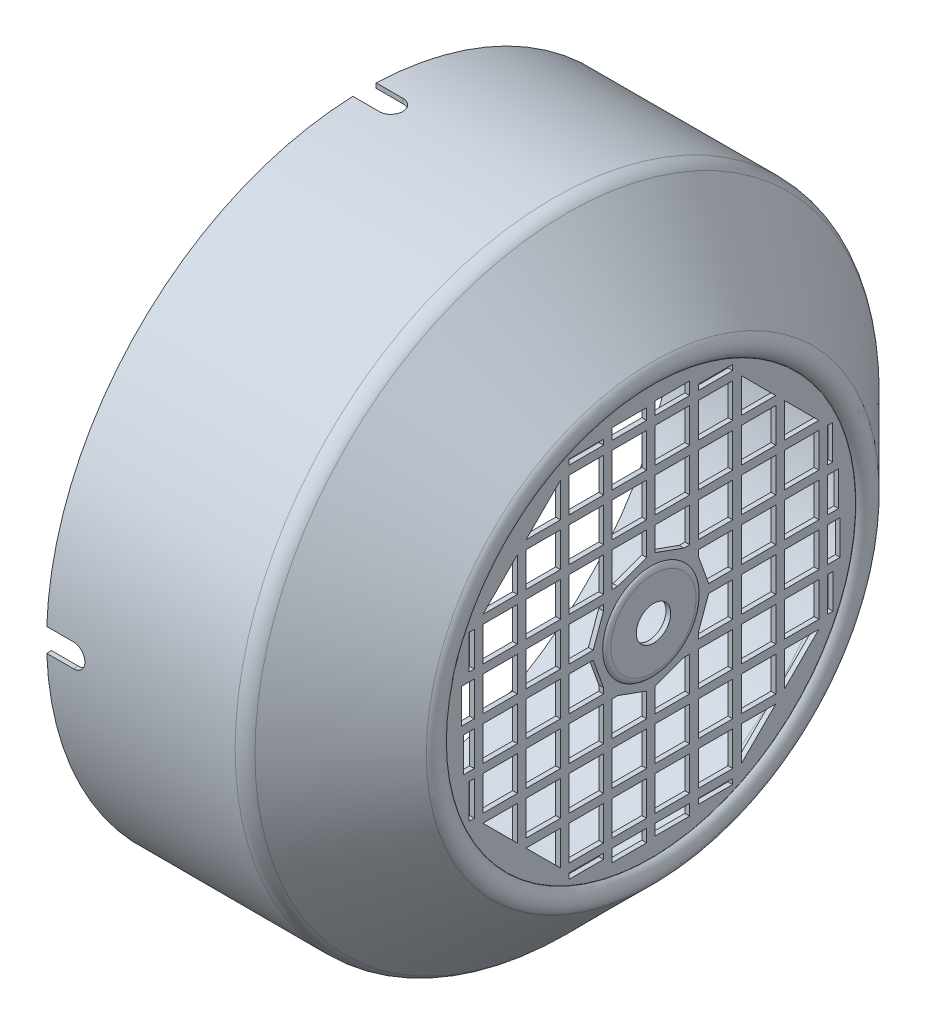
SolidWorks part; units mm, degrees
ref_plane "Plan de face" through (0, 0, 0) normal (0, 0, 1) x (1, 0, 0)
ref_plane "Plan de dessus" through (0, 0, 0) normal (0, 1, 0) x (1, 0, 0)
ref_plane "Plan de droite" through (0, 0, 0) normal (1, 0, 0) x (0, 0, -1)
sketch "Esquisse1" plane through (0, 0, 0) normal (0, 0, 1) x (1, 0, 0)
  line L0 (-18.5477, 0) -> (43.015, 0) construction
  line L1 (0, 4) -> (0, 9.9)
  line L2 (-0.9673, 9.9) -> (0.1952, 9.9) construction
  line L3 (-0.6, 10.5) -> (-0.6, 9.7263) construction
  line L5 (-0.6, 10.5) -> (-0.6, 47.5)
  line L6 (0.1556, 51.8052) -> (-19.7341, 71.6949)
  line L7 (-22.2089, 72.72) -> (-66, 72.72)
  arc A0 (0, 9.9) -> (-0.6, 10.5) centre (-0.6, 9.9) ccw
  arc A1 (-0.6, 47.5) -> (-0.1059, 48.4704) centre (0.6, 47.5) cw
  arc A2 (-0.1059, 48.4704) -> (0.1556, 51.8052) centre (-1.4, 50.2495) ccw
  arc A3 (-19.7341, 71.6949) -> (-22.2089, 72.72) centre (-22.2089, 69.22) ccw
  dimension "D3" = 0.6
  dimension "D6" = 1.2
  dimension "D7" = 2.2
  dimension "D10" = 7
  dimension "D11" = 64.6
  dimension "D1" = 8
  dimension "D2" = 21
  dimension "D4" = 95
  dimension "D5" = 135
  dimension "D8" = 0.8
  dimension "D9" = 145.44
revolve "Révol.-Mince1" add sketch "Esquisse1" angle 360 about L0
sketch "Esquisse2" plane through (0.5, 0, 0) normal (1, 0, 0) x (0, 0, -1)
  line L0 (0, 50.1333) -> (0, -49.9158) construction
  line L1 (-50.8687, 0) -> (49.5666, 0) construction
  line L2 (-46.04, 20) -> (47.4421, 20) construction
  line L3 (-9, 29) -> (-1, 29)
  line L4 (-9, 29) -> (-9, 21)
  line L5 (-9, 21) -> (-1, 21)
  line L6 (-1, 29) -> (-1, 21)
  line L7 (-19, 29) -> (-19, 21)
  line L8 (-37.3485, 30) -> (37.978, 30) construction
  line L9 (-10, 48.0087) -> (-10, 0) construction
  line L10 (-11, 21) -> (-19, 21)
  line L11 (-11, 29) -> (-11, 21)
  line L12 (-11, 29) -> (-19, 29)
  line L13 (-1, 13.4124) -> (-1, 19)
  line L14 (-9, 11) -> (-9, 19)
  line L15 (-9, 19) -> (-1, 19)
  line L16 (-9, 11) -> (-7.7249, 11)
  line L17 (-11, 11) -> (-19, 11)
  line L18 (-19, 11) -> (-19, 19)
  line L19 (-11, 19) -> (-19, 19)
  line L20 (-11, 11) -> (-11, 19)
  line L21 (-19, 41) -> (-19, 42.2143)
  line L22 (-11, 41) -> (-19, 41)
  line L23 (-19, 42.2143) -> (-11, 42.2143)
  line L24 (-11, 42.2143) -> (-11, 41)
  line L25 (-9, 41) -> (-9, 43.5663)
  line L26 (-9, 41) -> (-1, 41)
  line L27 (-9, 43.5663) -> (-1, 43.5663)
  line L28 (-1, 43.5663) -> (-1, 41)
  line L29 (-11, 31) -> (-19, 31)
  line L30 (-11, 31) -> (-11, 39)
  line L31 (-11, 39) -> (-19, 39)
  line L32 (-19, 31) -> (-19, 39)
  line L33 (-1, 31) -> (-1, 39)
  line L34 (-9, 39) -> (-1, 39)
  line L35 (-9, 31) -> (-9, 39)
  line L36 (-9, 31) -> (-1, 31)
  line L37 (-49.3235, 10) -> (49.5666, 10) construction
  line L38 (-11, 9) -> (-11, 7.6741)
  line L39 (-13.4124, 1) -> (-19, 1)
  line L40 (-19, 9) -> (-19, 1)
  line L41 (-11, 9) -> (-19, 9)
  line L42 (-20, 44.3389) -> (-20, -2.7884) construction
  line L43 (-29, 9) -> (-21, 9)
  line L44 (-21, 9) -> (-21, 1)
  line L45 (-29, 1) -> (-21, 1)
  line L46 (-29, 9) -> (-29, 1)
  line L47 (-21, 39) -> (-29, 31)
  line L48 (-31, 29) -> (-39, 21)
  line L49 (-41, 19) -> (-42.2723, 19)
  line L50 (-42.2723, 19) -> (-42.2723, 11)
  line L51 (-21, 31) -> (-21, 39)
  line L52 (-42.2723, 11) -> (-41, 11)
  line L53 (-41, 9) -> (-43.9467, 9)
  line L54 (-29, 31) -> (-21, 31)
  line L55 (-29, 11) -> (-29, 19)
  line L56 (-29, 19) -> (-21, 19)
  line L57 (-21, 11) -> (-21, 19)
  line L58 (-29, 11) -> (-21, 11)
  line L59 (-31, 11) -> (-39, 11)
  line L60 (-39, 11) -> (-39, 19)
  line L61 (-31, 19) -> (-39, 19)
  line L62 (-31, 11) -> (-31, 19)
  line L63 (-29, 29) -> (-21, 29)
  line L64 (-29, 29) -> (-29, 21)
  line L65 (-29, 21) -> (-21, 21)
  line L66 (-21, 29) -> (-21, 21)
  line L67 (-43.9467, 9) -> (-43.9467, 1)
  line L68 (-31, 21) -> (-39, 21)
  line L69 (-31, 29) -> (-31, 21)
  line L70 (-43.9467, 1) -> (-41, 1)
  line L71 (-30, 40.5595) -> (-30, -1.5894) construction
  line L72 (-31, 9) -> (-31, 1)
  line L73 (-31, 1) -> (-39, 1)
  line L74 (-39, 9) -> (-39, 1)
  line L75 (-31, 9) -> (-39, 9)
  line L76 (-11, 7.6741) -> (-13.4124, 1)
  line L77 (-41, 9) -> (-41, 1)
  line L78 (-7.7249, 11) -> (-1, 13.4124)
  line L82 (-41, 11) -> (-41, 19)
  dimension "D1" = 8
  dimension "D2" = 8
  dimension "D3" = 2
  dimension "D4" = 42
  dimension "D5" = 2
  dimension "D6" = 2
  dimension "D7" = 2
  dimension "D8" = 2
  dimension "D9" = 2
extrude "Enlèv. mat.-Extru.1" cut sketch "Esquisse2" against normal through all
pattern_circular "Répétition circulaire1" count 4 over 360 about axis through (0, 0, 0) along (1, 0, 0) of "Enlèv. mat.-Extru.1"
ref_plane "Plan1" through (-44.1045, 73.82, 0) normal (0, 1, 0) x (0, 0, -1)
sketch "Esquisse3" plane through (-44.1045, 73.82, 0) normal (0, 1, 0) x (0, 0, -1)
  line L0 (2.7, 21.8955) -> (2.7, 15.6955)
  line L1 (73.82, 21.8955) -> (-73.82, 21.8955) construction
  line L2 (-2.7, 15.6955) -> (-2.7, 21.8955)
  line L3 (0, -25.5567) -> (0, -87.1194) construction
  line L4 (0, -13.5984) -> (0, 35.217) construction
  arc A0 (2.7, 15.6955) -> (-2.7, 15.6955) centre (0, 15.6955) cw
  dimension "D2" = 6.2
  dimension "D1" = 5.4
extrude "Enlèv. mat.-Extru.3" cut sketch "Esquisse3" along normal through all and the other way through all flip side to cut
pattern_circular "Répétition circulaire6" count 3 over 180 about axis through (-18.5477, 0, 0) along (1, 0, 0) of "Enlèv. mat.-Extru.3"
